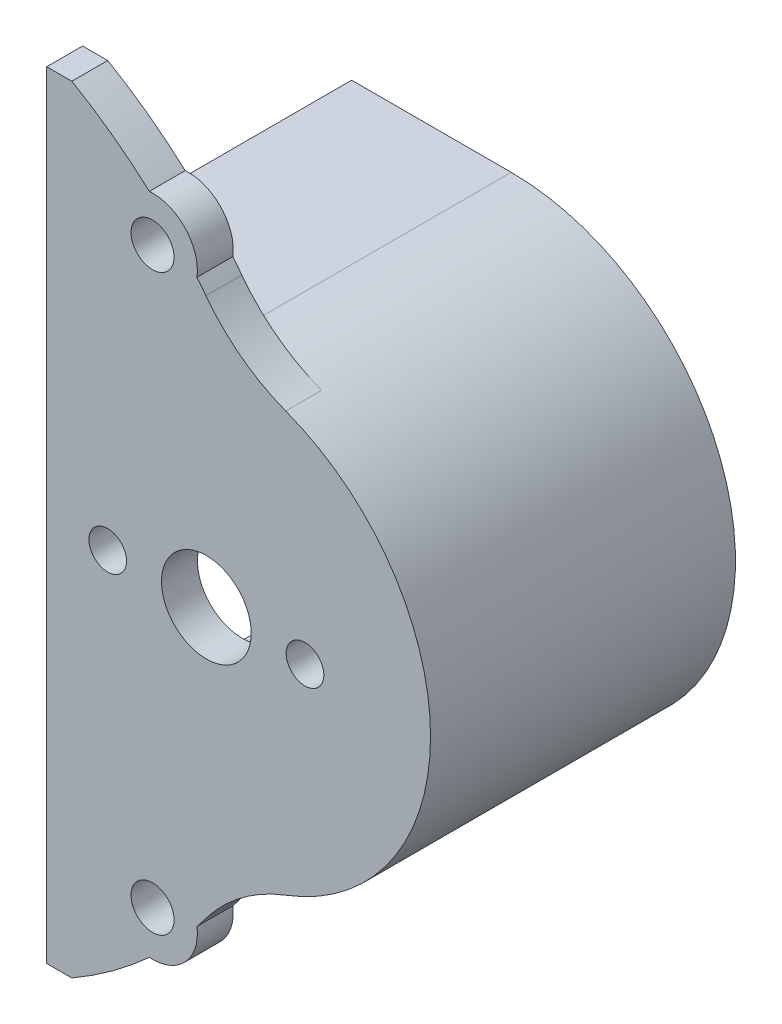
SolidWorks part; units mm, degrees
ref_plane "前视基准面" through (0, 0, 0) normal (0, 0, 1) x (1, 0, 0)
ref_plane "上视基准面" through (0, 0, 0) normal (0, 1, 0) x (1, 0, 0)
ref_plane "右视基准面" through (0, 0, 0) normal (1, 0, 0) x (0, 0, -1)
sketch "草图1" plane through (0, 0, 0) normal (0, 0, 1) x (1, 0, 0)
  line L0 (-17.3205, 10) -> (17.3205, 10) construction
  arc A0 (-17.3205, 10) -> (17.3205, 10) centre (0, 0) cw construction
  arc A1 (21.6506, 12.5) -> (-21.6506, 12.5) centre (0, 0) ccw
  arc A2 (12.9904, 7.5) -> (-12.9904, 7.5) centre (0, 0) ccw
  arc A3 (12.9904, 7.5) -> (21.6506, 12.5) centre (17.3205, 10) ccw
  arc A4 (-21.6506, 12.5) -> (-12.9904, 7.5) centre (-17.3205, 10) ccw
  point P4 (0, 20)
  dimension "D2" = 20
  dimension "D3" = 5
  dimension "D1" = 120
extrude "凸台-拉伸1" add sketch "草图1" along normal blind 2
sketch "草图2" plane through (0, 0, 2) normal (0, 0, 1) x (1, 0, 0)
  circle A0 centre (0, 20) radius 2.5
  circle A1 centre (-5.5, 20) radius 1.05
  circle A2 centre (5.5, 20) radius 1.05
  dimension "D1" = 5
  dimension "D2" = 20
  dimension "D3" = 5.5
  dimension "D4" = 11
  dimension "D5" = 2.1
extrude "切除-拉伸1" cut sketch "草图2" against normal blind 5
sketch "草图4" plane through (0, 0, 2) normal (0, 0, 1) x (1, 0, 0)
  circle A0 centre (-17.3205, 10) radius 1.1
  circle A1 centre (17.3205, 10) radius 1.1
  dimension "D1" = 2.2
  dimension "D2" = 2.2
extrude "切除-拉伸2" cut sketch "草图4" against normal blind 2
sketch "草图5" plane through (0, 0, 2) normal (0, 0, 1) x (1, 0, 0)
  arc A0 (-9.3633, 11.7188) -> (9.3633, 11.7188) centre (0, 20) ccw
  arc A1 (12.9904, 7.5) -> (-12.9904, 7.5) centre (0, 0) ccw construction
  arc A2 (21.6506, 12.5) -> (-21.6506, 12.5) centre (0, 0) ccw construction
  arc A3 (9.3633, 11.7188) -> (-9.3633, 11.7188) centre (0, 0) ccw
  arc A4 (12.3813, 21.7188) -> (-12.3813, 21.7188) centre (0, 0) ccw
  arc A5 (12.3813, 21.7188) -> (-12.3813, 21.7188) centre (0, 20) ccw
  dimension "D1" = 25
extrude "凸台-拉伸2" add sketch "草图5" against normal up to surface (2 mm away) up to face at (-16.2205, 10, 0)
sketch "草图6" plane through (0, 0, 2) normal (0, 0, 1) x (1, 0, 0)
  circle A0 centre (0, 20) radius 12.5
extrude "切除-拉伸3" cut sketch "草图6" against normal blind 10 flip side to cut
sketch "草图7" plane through (0, 0, 2) normal (0, 0, 1) x (1, 0, 0)
  line L0 (-7.5, 10) -> (-7.5, -5)
  line L1 (-7.5, 45) -> (7.5, 45)
  line L2 (-7.5, 45) -> (-7.5, 30)
  line L3 (-7.5, -5) -> (7.5, -5)
  line L4 (7.5, 45) -> (7.5, 30)
  line L5 (-7.5, 45) -> (-3.5918, 31.9728) construction
  line L6 (-7.5, -5) -> (0, 20) construction
  line L7 (0, 20) -> (7.5, -5) construction
  line L8 (3.5918, 31.9728) -> (7.5, 45) construction
  line L9 (7.5, 10) -> (7.5, -5)
  circle A0 centre (0, 20) radius 12.5 construction
  arc A1 (-7.5, 10) -> (7.5, 10) centre (0, 20) ccw
  arc A2 (7.5, 30) -> (-7.5, 30) centre (0, 20) ccw
  point P0 (0, 20)
  dimension "D1" = 15
  dimension "D2" = 50
extrude "凸台-拉伸3" add sketch "草图7" against normal up to surface (2 mm away) up to face at (6.55, 20, 0)
sketch "草图8" plane through (0, 0, 2) normal (0, 0, 1) x (1, 0, 0)
  circle A0 centre (-3, 4) radius 1.2
  circle A1 centre (-3, 36) radius 1.2
  dimension "D1" = 2.4
  dimension "D2" = 2.4
extrude "切除-拉伸4" cut sketch "草图8" against normal blind 10
sketch "草图9" plane through (0, 0, 2) normal (0, 0, 1) x (1, 0, 0)
  arc A8 (4.4271, 8.3102) -> (4.4271, 31.6898) centre (0, 20) ccw
  arc A9 (4.4271, 8.3102) -> (-0.0223, 4.9703) centre (7.9687, -1.0416) ccw
  arc A10 (-0.5217, 4.3285) -> (-0.0223, 4.9703) centre (-20, 20) ccw
  arc A11 (-3.1779, 1.5063) -> (-0.5217, 4.3285) centre (-3, 4) ccw
  arc A12 (-3.1779, 38.4937) -> (-3.1779, 1.5063) centre (-20, 20) ccw
  arc A13 (-0.5217, 35.6715) -> (-3.1779, 38.4937) centre (-3, 36) ccw
  arc A14 (-0.0223, 35.0297) -> (-0.5217, 35.6715) centre (-20, 20) ccw
  arc A15 (-0.0223, 35.0297) -> (4.4271, 31.6898) centre (7.9688, 41.0416) ccw
  arc A16 (4.4271, 8.3102) -> (4.4271, 31.6898) centre (0, 20) ccw
  arc A17 (4.4271, 8.3102) -> (-0.0223, 4.9703) centre (7.9687, -1.0416) ccw
  arc A18 (-0.5217, 4.3285) -> (-0.0223, 4.9703) centre (-20, 20) ccw
  arc A19 (-3.1779, 1.5063) -> (-0.5217, 4.3285) centre (-3, 4) ccw
  arc A20 (-3.1779, 38.4937) -> (-3.1779, 1.5063) centre (-20, 20) ccw
  arc A21 (-0.5217, 35.6715) -> (-3.1779, 38.4937) centre (-3, 36) ccw
  arc A22 (-0.0223, 35.0297) -> (-0.5217, 35.6715) centre (-20, 20) ccw
  arc A23 (-0.0223, 35.0297) -> (4.4271, 31.6898) centre (7.9688, 41.0416) ccw
  dimension "D1" = 0
extrude "切除-拉伸5" cut sketch "草图9" against normal blind 14 flip side to cut
fillet "圆角1" [suppressed] radius 2
sketch "草图10" plane through (0, 0, 0) normal (0, 0, -1) x (-1, 0, 0)
  line L0 (7.5, 35.8253) -> (7.5, 4.1747)
  line L1 (7.5, 30) -> (7.5, 41.6506) construction
  line L2 (7.5, -1.6506) -> (7.5, 10) construction
  line L3 (7.5, 4.1747) -> (36.8241, 12.604)
  line L4 (36.8241, 12.604) -> (7.5, 35.8253)
extrude "切除-拉伸6" cut sketch "草图10" against normal blind 10
sketch "草图11" plane through (-7.5, 0, 0) normal (-1, 0, 0) x (0, 0, 1)
  line L4 (2, 41.6506) -> (0, 41.6506)
  line L5 (2, -1.6506) -> (2, 41.6506)
  line L6 (2, 41.6506) -> (0, 41.6506)
  line L7 (0, 41.6506) -> (0, -1.6506)
  line L9 (2, -1.6506) -> (2, 41.6506)
  line L11 (0, 41.6506) -> (0, -1.6506)
  line L14 (0, -1.6506) -> (2, -1.6506)
  line L15 (0, -1.6506) -> (2, -1.6506)
  dimension "D1" = 0
extrude "凸台-拉伸4" add sketch "草图11" along normal blind 1.4
sketch "草图12" plane through (0, 0, 0) normal (0, 0, -1) x (-1, 0, 0)
  line L0 (0, 32.5) -> (8.9, 32.5)
  line L1 (8.9, 41.6506) -> (8.9, -1.6506) construction
  line L2 (0, 7.5) -> (8.9, 7.5)
  arc A0 (0, 32.5) -> (0, 7.5) centre (0, 20) ccw
extrude "拉伸-薄壁1" add sketch "草图12" along normal blind 15 thin
